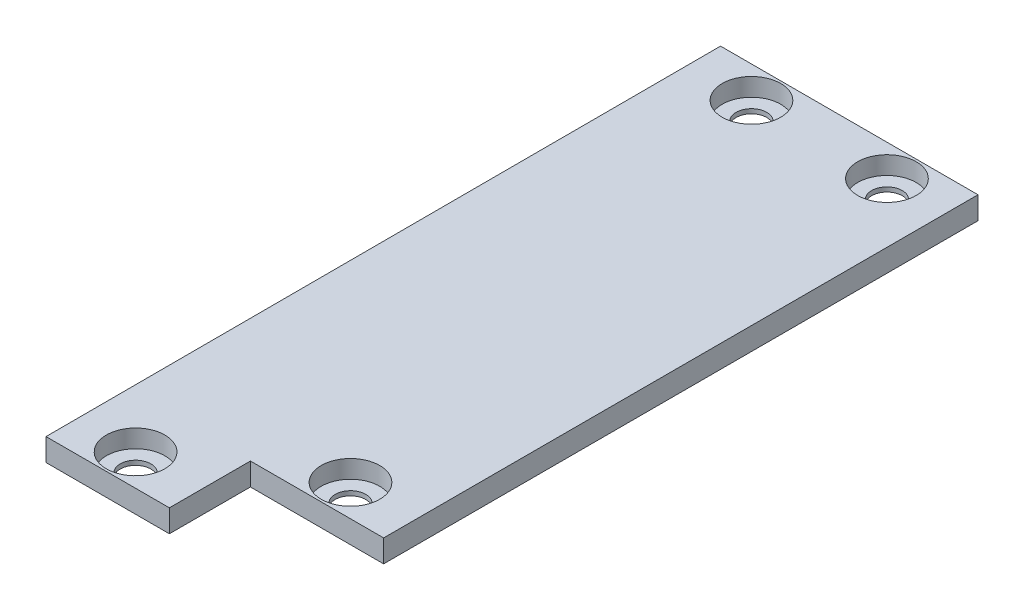
SolidWorks part; units mm, degrees
ref_plane "Front Plane" through (0, 0, 0) normal (0, 0, 1) x (1, 0, 0)
ref_plane "Top Plane" through (0, 0, 0) normal (0, 1, 0) x (1, 0, 0)
ref_plane "Right Plane" through (0, 0, 0) normal (1, 0, 0) x (0, 0, -1)
sketch "Sketch1" plane through (0, 0, 0) normal (0, 1, 0) x (1, 0, 0)
  line L0 (0, 0) -> (13.9, 0)
  line L1 (13.9, 0) -> (13.9, 9)
  line L2 (13.9, 9) -> (28.49, 9)
  line L3 (28.49, 9) -> (28.49, 76)
  line L4 (28.49, 76) -> (-0.1, 76)
  line L5 (-0.1, 76) -> (0, 0)
extrude "Boss-Extrude1" add sketch "Sketch1" along normal blind 2.5 contours L5 L0 L1 L2 L3 L4
sketch "Sketch2" plane through (0, 2.5, 0) normal (0, 1, 0) x (1, 0, 0)
  line L1 (-0.1, 76) -> (0, 0) construction
  line L2 (-0.0053, 4) -> (6.4447, 4)
  line L3 (28.49, 9) -> (28.49, 76) construction
  line L4 (28.49, 13) -> (21.31, 13)
  line L5 (-0.0947, 72) -> (6.8353, 72)
  line L6 (28.49, 72) -> (21.88, 72)
hole_wizard "CBORE for M3 Cheese Head Screw1" positions "Sketch3" profile "Sketch4" counterbore size "M3" standard "AS" end condition up to next
sketch "Sketch3" plane through (0, 2.5, 0) normal (0, 1, 0) x (1, 0, 0)
  point P0 (6.8353, 72)
  point P3 (21.88, 72)
  point P6 (21.31, 13)
  point P9 (6.4447, 4)
sketch "Sketch4" plane through (6.8353, 2.5, -72) normal (1, 0, 0) x (0, 0, 1)
  line L0 (0, 0) -> (0, 2.5)
  line L1 (0, 2.5) -> (1.7, 2.5)
  line L3 (1.7, 2.5) -> (1.7, 2)
  line L4 (1.7, 2) -> (3.25, 2)
  line L5 (3.25, 2) -> (3.25, 0)
  line L7 (3.25, 0) -> (0, 0)
  line L11 (0, -6.35) -> (0, 107.95) construction
  dimension "Thru Hole Dia." = 3.4
  dimension "Thru Hole Depth" = 2.5
  dimension "C'Bore Dia." = 6.5
  dimension "C'Bore Depth" = 2
sketch "Sketch5" plane through (0, 2.5, 0) normal (0, 1, 0) x (1, 0, 0)
  line L0 (-0.1, 76) -> (-0.0993, 75.5)
  line L1 (-0.1, 76) -> (0, 0) construction
  line L2 (28.49, 76) -> (28.49, 75.5)
  line L3 (28.49, 9) -> (28.49, 76) construction
  line L4 (-0.0993, 75.5) -> (28.49, 75.5)
  line L5 (-0.1, 76) -> (28.49, 76)
extrude "Cut-Extrude1" cut sketch "Sketch5" against normal blind 10
sketch "Sketch6" plane through (0, 2.5, 0) normal (0, 1, 0) x (1, 0, 0)
  line L0 (28.49, 9) -> (28.49, 9.5)
  line L1 (28.49, 9) -> (28.49, 75.5) construction
  line L2 (13.9, 9) -> (13.9, 9.5)
  line L3 (13.9, 9.5) -> (28.49, 9.5)
  line L4 (13.9, 9) -> (28.49, 9)
extrude "Cut-Extrude2" cut sketch "Sketch6" against normal blind 10
sketch "Sketch7" plane through (0, 2.5, 0) normal (0, 1, 0) x (1, 0, 0)
  line L0 (13.9, 0) -> (13.9, 0.5)
  line L1 (13.9, 0) -> (13.9, 9.5) construction
  line L2 (0, 0) -> (-0.0007, 0.5)
  line L3 (-0.0993, 75.5) -> (0, 0) construction
  line L4 (-0.0007, 0.5) -> (13.9, 0.5)
  line L5 (0, 0) -> (13.9, 0)
extrude "Cut-Extrude3" cut sketch "Sketch7" against normal blind 10
sketch "Sketch8" plane through (0, 2.5, 0) normal (0, 1, 0) x (1, 0, 0)
  line L0 (13.9, 9.5) -> (13.7, 9.5)
  line L1 (13.9, 0.5) -> (13.7, 0.5)
  line L2 (13.9, 0.5) -> (-0.0007, 0.5) construction
  line L3 (13.7, 0.5) -> (13.7, 9.5)
  line L4 (13.9, 9.5) -> (13.9, 0.5)
extrude "Cut-Extrude4" cut sketch "Sketch8" against normal blind 10
